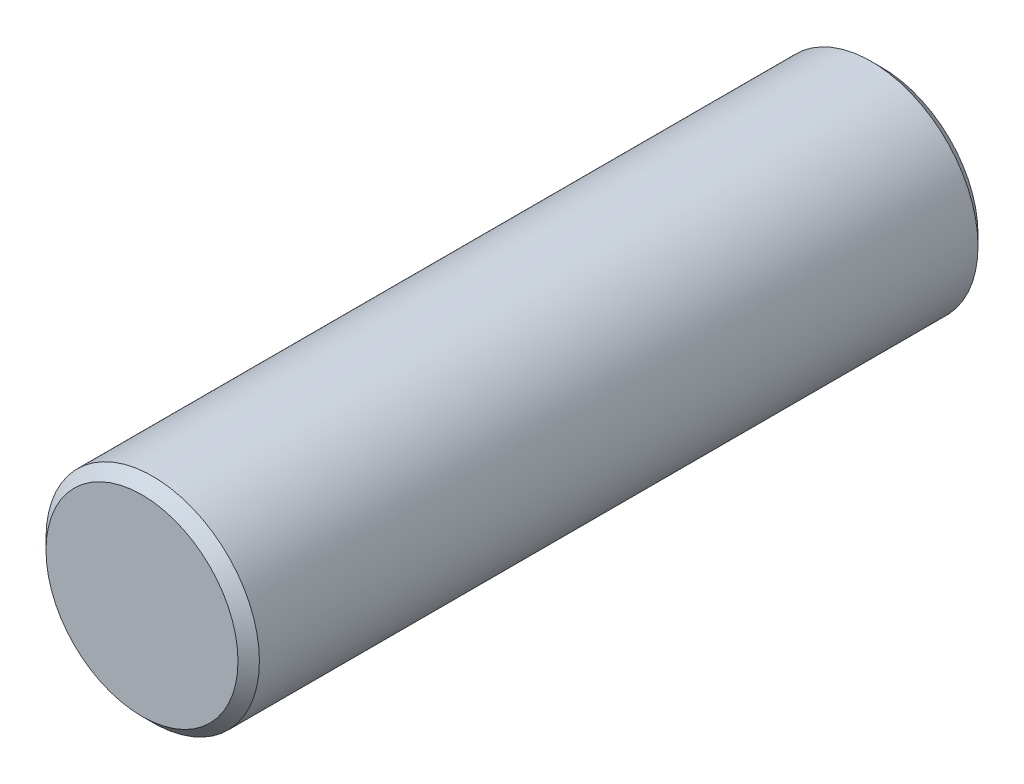
SolidWorks part; units mm, degrees
ref_plane "정면" through (0, 0, 0) normal (0, 0, 1) x (1, 0, 0)
ref_plane "윗면" through (0, 0, 0) normal (0, 1, 0) x (1, 0, 0)
ref_plane "우측면" through (0, 0, 0) normal (1, 0, 0) x (0, 0, -1)
sketch "스케치1" plane through (0, 0, 0) normal (0, 0, 1) x (1, 0, 0)
  circle A0 centre (0, 0) radius 1.99
  dimension "D1" = 3.98
extrude "보스-돌출1" add sketch "스케치1" along normal mid plane 13.8 contours A0
chamfer "모따기1" distance 0.2 angle 45 2 edges at (1.99, 0, -6.9) (1.99, 0, 6.9)
